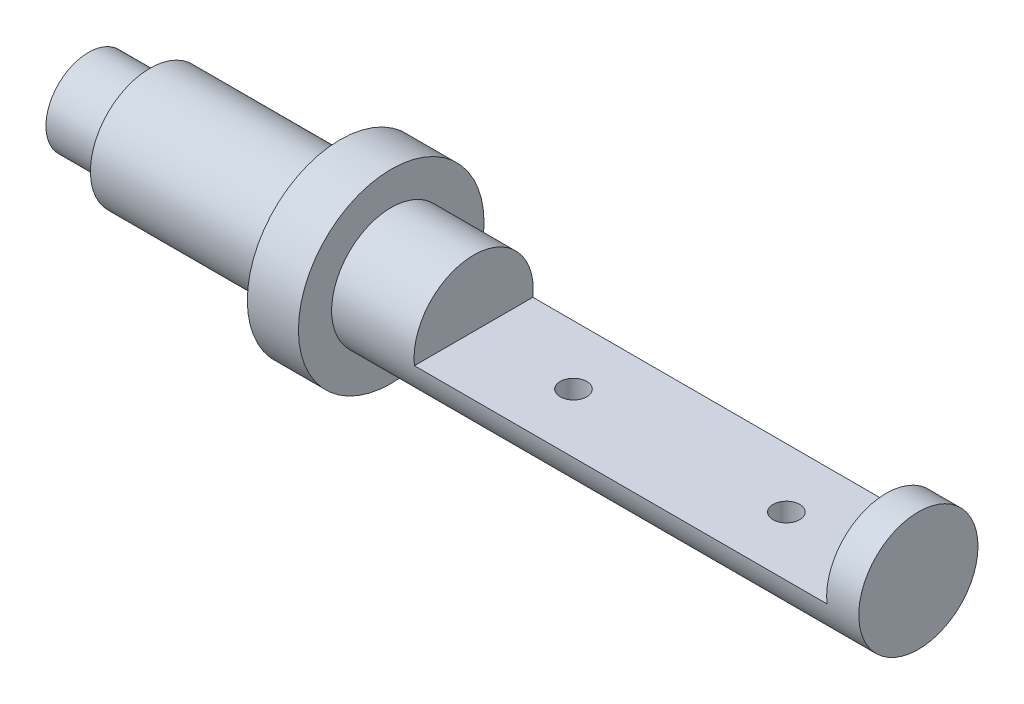
SolidWorks part; units mm, degrees
ref_plane "Front Plane" through (0, 0, 0) normal (0, 0, 1) x (1, 0, 0)
ref_plane "Top Plane" through (0, 0, 0) normal (0, 1, 0) x (1, 0, 0)
ref_plane "Right Plane" through (0, 0, 0) normal (1, 0, 0) x (0, 0, -1)
sketch "Sketch1" plane through (0, 0, 0) normal (0, 0, 1) x (1, 0, 0)
  line L0 (0, 0) -> (0, 20)
  line L1 (0, 20) -> (28.9, 20)
  line L2 (28.9, 20) -> (28.9, 28)
  line L3 (28.9, 28) -> (118.2, 28)
  line L4 (118.2, 28) -> (118.2, 43.6)
  line L5 (118.2, 43.6) -> (142.2, 43.6)
  line L6 (142.2, 43.6) -> (142.2, 28)
  line L7 (142.2, 28) -> (389.8, 28)
  line L8 (389.8, 28) -> (389.8, 0)
  line L9 (389.8, 0) -> (0, 0)
  dimension "D1" = 20
  dimension "D2" = 28
  dimension "D3" = 43.6
  dimension "D4" = 247.6
  dimension "D5" = 28.9
  dimension "D6" = 89.3
  dimension "D7" = 24
revolve "Revolve1" add sketch "Sketch1" angle 360 about L9
sketch "Sketch2" plane through (0, 0, 0) normal (0, 0, 1) x (1, 0, 0)
  line L0 (389.8, 28) -> (142.2, 28) construction
  line L1 (180.9, 28) -> (374.7, 28)
  line L2 (180.9, 28) -> (180.9, -3.1)
  line L3 (180.9, -3.1) -> (374.7, -3.1)
  line L4 (374.7, 28) -> (374.7, -3.1)
  line L5 (389.8, -28) -> (389.8, 28) construction
  dimension "D1" = 15.1
  dimension "D2" = 31.1
  dimension "D3" = 193.8
extrude "Cut-Extrude1" cut sketch "Sketch2" against normal through all both and the other way through all
hole_wizard "Hole1" positions "Sketch3" profile "Sketch4" legacy end condition up to next
sketch "Sketch3" plane through (0, -3.1, 0) normal (0, 1, 0) x (1, 0, 0)
  line L0 (180.9, -28) -> (180.9, 28) construction
  point P0 (227.8, 0)
  point P2 (327.8, 0)
  dimension "D1" = 100
  dimension "D2" = 46.9
sketch "Sketch4" plane through (227.8, -3.1, 0) normal (1, 0, 0) x (0, 0, 1)
  line L0 (0, 0) -> (0, 24.9)
  line L1 (0, 24.9) -> (6.25, 24.9)
  line L2 (6.25, 24.9) -> (6.25, 0)
  line L3 (6.25, 0) -> (0, 0)
  line L4 (0, 110) -> (0, -10) construction
  dimension "Diameter" = 12.5
  dimension "Depth" = 24.9
